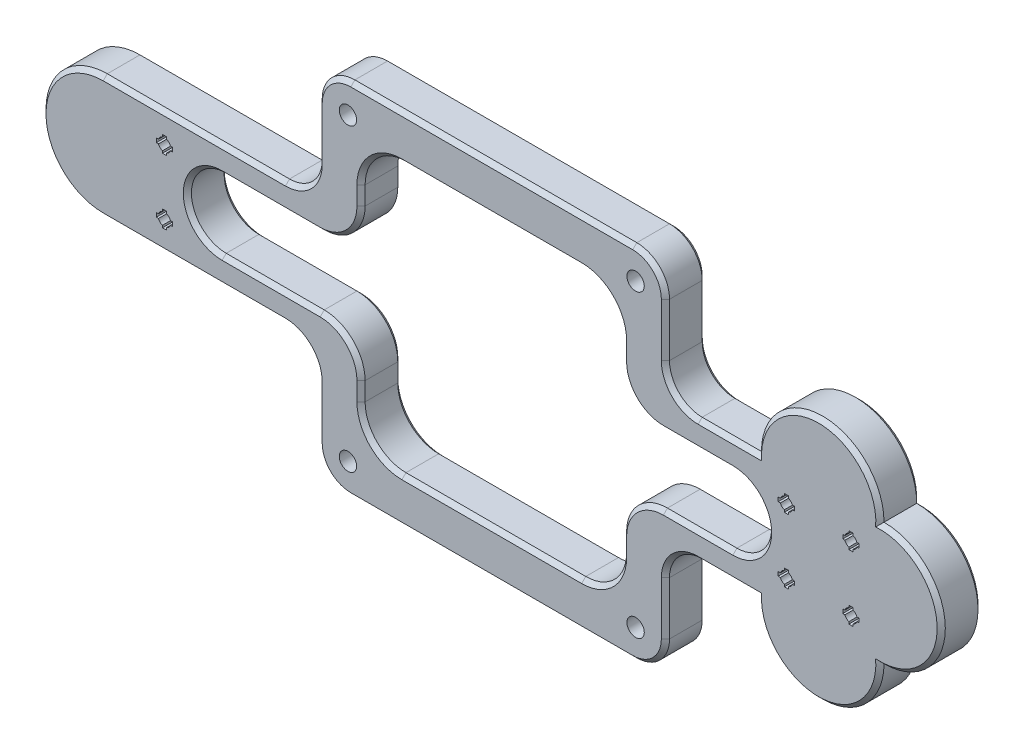
SolidWorks part; units mm, degrees
ref_plane "Front Plane" through (0, 0, 0) normal (0, 0, 1) x (1, 0, 0)
ref_plane "Top Plane" through (0, 0, 0) normal (0, 1, 0) x (1, 0, 0)
ref_plane "Right Plane" through (0, 0, 0) normal (1, 0, 0) x (0, 0, -1)
sketch "Sketch1" plane through (0, 0, 0) normal (0, 0, 1) x (1, 0, 0)
  line L0 (-83.1, -1.5) -> (-60.5, -1.5)
  line L5 (-60.5, -60.5) -> (24.5, -60.5)
  line L6 (-60.5, -60.5) -> (-60.5, 27.5)
  line L7 (44.9072, -16.5) -> (118.6549, -16.5) construction
  line L8 (62, 0.7794) -> (62, -22.1936) construction
  line L9 (69.4, -10.6) -> (70.4, -10.6)
  line L10 (69.4, -10.6) -> (69.4, -10.0671)
  line L11 (69.4, -6.6) -> (70.4, -6.6)
  line L12 (70.4, -10.6) -> (70.4, -10.0671)
  line L13 (69.4, -10.6) -> (70.4, -6.6) construction
  line L14 (69.4, -6.6) -> (70.4, -10.6) construction
  line L15 (67.9, -9.1) -> (68.4329, -9.1)
  line L16 (67.9, -9.1) -> (67.9, -8.1)
  line L17 (67.9, -8.1) -> (68.4329, -8.1)
  line L18 (71.9, -9.1) -> (71.9, -8.1)
  line L19 (67.9, -9.1) -> (71.9, -8.1) construction
  line L20 (67.9, -8.1) -> (71.9, -9.1) construction
  line L21 (70.4, -7.1329) -> (70.4, -6.6)
  line L22 (71.3671, -8.1) -> (71.9, -8.1)
  line L23 (69.4, -7.1329) -> (69.4, -6.6)
  line L24 (71.3671, -9.1) -> (71.9, -9.1)
  line L25 (56.1, -9.1) -> (56.1, -8.1)
  line L26 (56.1, -8.1) -> (55.5671, -8.1)
  line L27 (54.6, -7.1329) -> (54.6, -6.6)
  line L28 (54.6, -6.6) -> (53.6, -6.6)
  line L29 (53.6, -7.1329) -> (53.6, -6.6)
  line L30 (52.6329, -8.1) -> (52.1, -8.1)
  line L31 (52.1, -9.1) -> (52.1, -8.1)
  line L32 (52.6329, -9.1) -> (52.1, -9.1)
  line L33 (53.6, -10.6) -> (53.6, -10.0671)
  line L34 (54.6, -10.6) -> (53.6, -10.6)
  line L35 (54.6, -10.6) -> (54.6, -10.0671)
  line L36 (56.1, -9.1) -> (55.5671, -9.1)
  line L37 (56.1, -23.9) -> (55.5671, -23.9)
  line L38 (54.6, -22.4) -> (54.6, -22.9329)
  line L39 (54.6, -22.4) -> (53.6, -22.4)
  line L40 (53.6, -22.4) -> (53.6, -22.9329)
  line L41 (52.6329, -23.9) -> (52.1, -23.9)
  line L42 (52.1, -23.9) -> (52.1, -24.9)
  line L43 (52.6329, -24.9) -> (52.1, -24.9)
  line L44 (53.6, -25.8671) -> (53.6, -26.4)
  line L45 (54.6, -26.4) -> (53.6, -26.4)
  line L46 (54.6, -25.8671) -> (54.6, -26.4)
  line L47 (56.1, -24.9) -> (55.5671, -24.9)
  line L48 (56.1, -23.9) -> (56.1, -24.9)
  line L49 (67.9, -23.9) -> (67.9, -24.9)
  line L50 (67.9, -24.9) -> (68.4329, -24.9)
  line L51 (69.4, -25.8671) -> (69.4, -26.4)
  line L52 (69.4, -26.4) -> (70.4, -26.4)
  line L53 (70.4, -25.8671) -> (70.4, -26.4)
  line L54 (71.3671, -24.9) -> (71.9, -24.9)
  line L55 (71.9, -23.9) -> (71.9, -24.9)
  line L56 (71.3671, -23.9) -> (71.9, -23.9)
  line L57 (70.4, -22.4) -> (70.4, -22.9329)
  line L58 (69.4, -22.4) -> (70.4, -22.4)
  line L59 (69.4, -22.4) -> (69.4, -22.9329)
  line L60 (67.9, -23.9) -> (68.4329, -23.9)
  line L61 (47, -31.5) -> (77, -31.5)
  line L62 (47, -31.5) -> (47, -1.5)
  line L63 (47, -1.5) -> (77, -1.5)
  line L64 (77, -31.5) -> (77, -1.5)
  line L65 (47, -31.5) -> (77, -1.5) construction
  line L66 (47, -1.5) -> (77, -31.5) construction
  line L67 (-98.6, -10.6) -> (-97.6, -10.6)
  line L68 (-98.6, -10.6) -> (-98.6, -10.0671)
  line L69 (-98.6, -6.6) -> (-97.6, -6.6)
  line L70 (-97.6, -10.6) -> (-97.6, -10.0671)
  line L71 (-100.1, -9.1) -> (-99.5671, -9.1)
  line L72 (-100.1, -9.1) -> (-100.1, -8.1)
  line L73 (-100.1, -8.1) -> (-99.5671, -8.1)
  line L74 (-96.1, -9.1) -> (-96.1, -8.1)
  line L75 (-97.6, -7.1329) -> (-97.6, -6.6)
  line L76 (-96.6329, -8.1) -> (-96.1, -8.1)
  line L77 (-98.6, -7.1329) -> (-98.6, -6.6)
  line L78 (-96.6329, -9.1) -> (-96.1, -9.1)
  line L79 (-100.1, -23.9) -> (-100.1, -24.9)
  line L80 (-100.1, -24.9) -> (-99.5671, -24.9)
  line L81 (-98.6, -25.8671) -> (-98.6, -26.4)
  line L82 (-98.6, -26.4) -> (-97.6, -26.4)
  line L83 (-97.6, -25.8671) -> (-97.6, -26.4)
  line L84 (-96.6329, -24.9) -> (-96.1, -24.9)
  line L85 (-96.1, -23.9) -> (-96.1, -24.9)
  line L86 (-96.6329, -23.9) -> (-96.1, -23.9)
  line L87 (-97.6, -22.4) -> (-97.6, -22.9329)
  line L88 (-98.6, -22.4) -> (-97.6, -22.4)
  line L89 (-98.6, -22.4) -> (-98.6, -22.9329)
  line L90 (-100.1, -23.9) -> (-99.5671, -23.9)
  line L91 (-98.1, -8.6) -> (-98.1, -24.4) construction
  line L92 (-60.5, 27.5) -> (24.5, 27.5)
  line L93 (-113.1, -31.5) -> (-83.1, -31.5)
  line L94 (-113.1, -31.5) -> (-113.1, -1.5)
  line L95 (-113.1, -1.5) -> (-83.1, -1.5)
  line L96 (-83.1, -31.5) -> (-83.1, -1.5)
  line L97 (-113.1, -31.5) -> (-83.1, -1.5) construction
  line L98 (-113.1, -1.5) -> (-83.1, -31.5) construction
  line L99 (24.5, -60.5) -> (24.5, 27.5)
  line L100 (-60.5, -60.5) -> (24.5, 27.5) construction
  line L101 (-60.5, 27.5) -> (24.5, -60.5) construction
  line L102 (-83.1, -31.5) -> (-60.5, -31.5)
  line L103 (47, -1.5) -> (24.5, -1.5)
  line L104 (47, -31.5) -> (24.5, -31.5)
  arc A2 (69.4, -7.1329) -> (68.4329, -8.1) centre (69.9, -8.6) ccw
  arc A3 (68.4329, -9.1) -> (69.4, -10.0671) centre (69.9, -8.6) ccw
  arc A4 (71.3671, -8.1) -> (70.4, -7.1329) centre (69.9, -8.6) ccw
  arc A5 (70.4, -10.0671) -> (71.3671, -9.1) centre (69.9, -8.6) ccw
  arc A6 (54.6, -7.1329) -> (55.5671, -8.1) centre (54.1, -8.6) cw
  arc A7 (52.6329, -8.1) -> (53.6, -7.1329) centre (54.1, -8.6) cw
  arc A8 (53.6, -10.0671) -> (52.6329, -9.1) centre (54.1, -8.6) cw
  arc A9 (55.5671, -9.1) -> (54.6, -10.0671) centre (54.1, -8.6) cw
  arc A10 (55.5671, -23.9) -> (54.6, -22.9329) centre (54.1, -24.4) ccw
  arc A11 (53.6, -22.9329) -> (52.6329, -23.9) centre (54.1, -24.4) ccw
  arc A12 (52.6329, -24.9) -> (53.6, -25.8671) centre (54.1, -24.4) ccw
  arc A13 (54.6, -25.8671) -> (55.5671, -24.9) centre (54.1, -24.4) ccw
  arc A14 (69.4, -25.8671) -> (68.4329, -24.9) centre (69.9, -24.4) cw
  arc A15 (71.3671, -24.9) -> (70.4, -25.8671) centre (69.9, -24.4) cw
  arc A16 (70.4, -22.9329) -> (71.3671, -23.9) centre (69.9, -24.4) cw
  arc A17 (68.4329, -23.9) -> (69.4, -22.9329) centre (69.9, -24.4) cw
  arc A18 (47, -1.5) -> (77, -1.5) centre (62, -1.5) cw
  arc A19 (77, -1.5) -> (77, -31.5) centre (77, -16.5) cw
  arc A20 (77, -31.5) -> (47, -31.5) centre (62, -31.5) cw
  arc A21 (-98.6, -7.1329) -> (-99.5671, -8.1) centre (-98.1, -8.6) ccw
  arc A22 (-99.5671, -9.1) -> (-98.6, -10.0671) centre (-98.1, -8.6) ccw
  arc A23 (-96.6329, -8.1) -> (-97.6, -7.1329) centre (-98.1, -8.6) ccw
  arc A24 (-97.6, -10.0671) -> (-96.6329, -9.1) centre (-98.1, -8.6) ccw
  arc A25 (-98.6, -25.8671) -> (-99.5671, -24.9) centre (-98.1, -24.4) cw
  arc A26 (-96.6329, -24.9) -> (-97.6, -25.8671) centre (-98.1, -24.4) cw
  arc A27 (-97.6, -22.9329) -> (-96.6329, -23.9) centre (-98.1, -24.4) cw
  arc A28 (-99.5671, -23.9) -> (-98.6, -22.9329) centre (-98.1, -24.4) cw
  arc A29 (-113.1, -1.5) -> (-113.1, -31.5) centre (-113.1, -16.5) ccw
  circle A30 centre (-53.2, 20.2) radius 2.125
  circle A31 centre (17.2, 20.2) radius 2.125
  circle A32 centre (17.2, -53.2) radius 2.125
  circle A33 centre (-53.2, -53.2) radius 2.125
  point P0 (-18, -16.5)
  point P83 (62, -16.5)
  point P128 (-98.1, -16.5)
  dimension "D4" = 4.25
  dimension "D2" = 85
  dimension "D3" = 88
  dimension "D5" = 30
  dimension "D6" = 30
  dimension "D7" = 152.2
  dimension "D8" = 7.3
  dimension "D9" = 7.9
  dimension "D10" = 15.8
  dimension "D11" = 7.9
  dimension "D12" = 15.8
  dimension "D13" = 7.3
  dimension "D14" = 7.3
  dimension "D15" = 7.3
  dimension "D16" = 80
extrude "Boss-Extrude1" add sketch "Sketch1" along normal blind 10
fillet "Fillet2" radius 8 8 edges at (-60.5, -1.5, 5) (-60.5, 27.5, 5) (24.5, 27.5, 5) (24.5, -1.5, 5) (24.5, -31.5, 5) (24.5, -60.5, 5) (-60.5, -31.5, 5) (-60.5, -60.5, 5)
chamfer "Chamfer1" distance 1 angle 45 25 edges at (62, 13.5, 0) (62, 13.5, 10) (92, -16.5, 0) (92, -16.5, 10) (62, -46.5, 0) (62, -46.5, 10) (-128.1, -16.5, 10) (-90.8, -1.5, 10) (-90.8, -31.5, 10) (39.75, -1.5, 10) (39.75, -31.5, 10) (26.8431, 0.8431, 10) (26.8431, -33.8431, 10) (24.5, 13, 10) (24.5, -46, 10) (22.1569, 25.1569, 10) (22.1569, -58.1569, 10) (-18, 27.5, 10) (-18, -60.5, 10) (-58.1569, 25.1569, 10) (-58.1569, -58.1569, 10) (-60.5, 13, 10) (-60.5, -46, 10) (-62.8431, 0.8431, 10) (-62.8431, -33.8431, 10)
sketch "Sketch2" plane through (0, 0, 0) normal (0, 0, -1) x (-1, 0, 0)
  circle A0 centre (-17.2, 20.2) radius 3.5
  circle A1 centre (-17.2, -53.2) radius 3.5
  circle A2 centre (53.2, -53.2) radius 3.5
  circle A3 centre (53.2, 20.2) radius 3.5
  point P6 (-17.2, 20.2)
  point P8 (-17.2, -53.2)
  point P12 (53.2, -53.2)
  point P16 (53.2, 20.2)
  dimension "D1" = 7
extrude "Cut-Extrude1" cut sketch "Sketch2" against normal blind 3
sketch "Sketch3" plane through (0, 0, 10) normal (0, 0, 1) x (1, 0, 0)
  line L0 (-84, -16.5) -> (41, -16.5) construction
  line L1 (-84, -8) -> (41, -8)
  line L2 (-84, -25) -> (41, -25)
  line L3 (-53.2, 20.2) -> (-53.2, -53.2) construction
  line L6 (-50, -49.5) -> (14, -49.5)
  line L7 (-50, -49.5) -> (-50, 16.5)
  line L8 (-50, 16.5) -> (14, 16.5)
  line L9 (14, -49.5) -> (14, 16.5)
  line L10 (-50, -49.5) -> (14, 16.5) construction
  line L11 (-50, 16.5) -> (14, -49.5) construction
  line L12 (-53.2, -53.2) -> (17.2, -53.2) construction
  line L13 (17.2, -53.2) -> (17.2, 20.2) construction
  line L14 (17.2, 20.2) -> (-53.2, 20.2) construction
  line L15 (-18, 20.2) -> (-18, -53.2) construction
  line L16 (-68.5, -2.5) -> (-68.5, -30.5) construction
  arc A0 (-84, -8) -> (-84, -25) centre (-84, -16.5) ccw
  arc A1 (41, -25) -> (41, -8) centre (41, -16.5) ccw
  point P2 (-21.5, -16.5)
  point P7 (-18, -16.5)
  point P22 (17.2, -16.5)
  point P23 (-18, 16.5)
  point P24 (41.1189, -16.5)
  point P30 (-68.5, -16.5)
  point P31 (-71.7183, -25)
  point P32 (0, 0)
  dimension "D5" = 3.5
  dimension "D1" = 17
  dimension "D2" = 125
  dimension "D3" = 64
  dimension "D4" = 66
extrude "Cut-Extrude2" cut sketch "Sketch3" against normal through all contours L1 A0 L2 L7 | L2 L9 L1 L7 | L1 L9 L8 L7 | L6 L9 L2 L7 | L2 A1 L1 L9
fillet "Fillet3" radius 10 8 edges at (14, 16.5, 5) (14, -8, 5) (14, -49.5, 5) (14, -25, 5) (-50, -49.5, 5) (-50, -25, 5) (-50, -8, 5) (-50, 16.5, 5)
chamfer "Chamfer2" distance 1 angle 45 59 edges at (-72, -8, 0) (-72, -8, 10) (32.5, -8, 10) (32.5, -8, 0) (-92.5, -16.5, 10) (-92.5, -16.5, 0) (49.5, -16.5, 10) (49.5, -16.5, 0) (32.5, -25, 0) (32.5, -25, 10) (-72, -25, 10) (-72, -25, 0) (16.9289, -5.0711, 0) (16.9289, -5.0711, 10) (14, 4.25, 10) (14, 4.25, 0) (11.0711, 13.5711, 0) (11.0711, 13.5711, 10) (16.9289, -27.9289, 0) (16.9289, -27.9289, 10) (-18, 16.5, 0) (-18, 16.5, 10) (14, -37.25, 0) (14, -37.25, 10) (-47.0711, 13.5711, 0) (-47.0711, 13.5711, 10) (11.0711, -46.5711, 0) (11.0711, -46.5711, 10) (-50, 4.25, 10) (-50, 4.25, 0) (-18, -49.5, 10) (-18, -49.5, 0) (-52.9289, -5.0711, 0) (-52.9289, -5.0711, 10) (-47.0711, -46.5711, 0) (-47.0711, -46.5711, 10) (-50, -37.25, 10) (-50, -37.25, 0) (-52.9289, -27.9289, 0) (-52.9289, -27.9289, 10) (40.25, -1.5, 0) (40.25, -31.5, 0) (26.8431, 0.8431, 0) (26.8431, -33.8431, 0) (24.5, 13, 0) (24.5, -46, 0) (22.1569, 25.1569, 0) (22.1569, -58.1569, 0) (-18, 27.5, 0) (-18, -60.5, 0) (-58.1569, 25.1569, 0) (-58.1569, -58.1569, 0) (-60.5, 13, 0) (-60.5, -46, 0) (-62.8431, 0.8431, 0) (-62.8431, -33.8431, 0) (-90.8, -1.5, 0) (-90.8, -31.5, 0) (-128.1, -16.5, 0)
